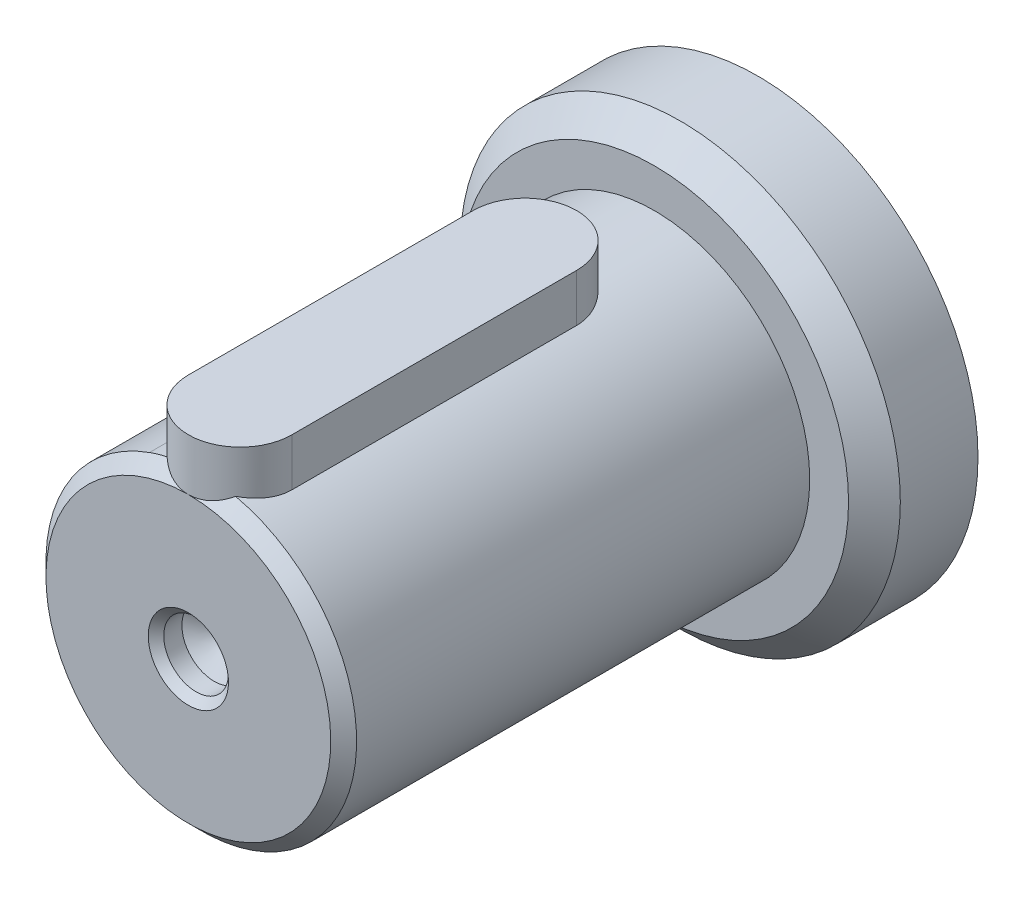
SolidWorks part; units mm, degrees
ref_plane "Plan de face" through (0, 0, 0) normal (0, 0, 1) x (1, 0, 0)
ref_plane "Plan de dessus" through (0, 0, 0) normal (0, 1, 0) x (1, 0, 0)
ref_plane "Plan de droite" through (0, 0, 0) normal (1, 0, 0) x (0, 0, -1)
sketch "Esquisse1" plane through (0, 0, 0) normal (0, 0, 1) x (1, 0, 0)
  circle A0 centre (0, 0) radius 8.5
  dimension "D1" = 17
extrude "Boss.-Extru.1" add sketch "Esquisse1" along normal blind 4
sketch "Esquisse2" plane through (0, 0, 4) normal (0, 0, 1) x (1, 0, 0)
  circle A0 centre (0, 0) radius 6
  dimension "D1" = 12
extrude "Boss.-Extru.2" add sketch "Esquisse2" along normal blind 18
chamfer "Chanfrein1" distance 1 angle 45 1 edges at (8.5, 0, 4)
chamfer "Chanfrein2" distance 0.5 angle 45 1 edges at (6, 0, 22)
ref_plane "Plan1" through (0, 6, 0) normal (0, 1, 0) x (1, 0, 0)
sketch "Esquisse3" plane through (0, 6, 0) normal (0, 1, 0) x (1, 0, 0)
  line L0 (0, -30.6066) -> (0, 7.4045) construction
  line L1 (0, -20) -> (0, -9) construction
  line L2 (-2, -20) -> (-2, -9)
  line L3 (2, -20) -> (2, -9)
  line L4 (-5.5, -22) -> (5.5, -22) construction
  line L5 (-9.0695, -7) -> (12.7701, -7) construction
  line L6 (-9.912, -22) -> (11.8854, -22) construction
  arc A0 (-2, -20) -> (2, -20) centre (0, -20) ccw
  arc A1 (2, -9) -> (-2, -9) centre (0, -9) ccw
  point P5 (0, -14.5)
  dimension "D1" = 4
  dimension "D2" = 15
extrude "Boss.-Extru.3" add sketch "Esquisse3" along normal blind 1.5 and the other way blind 1
hole_wizard "Trou pour taraudage pour trou taraudé M31" positions "Esquisse5" profile "Esquisse4" hole size "M3" standard "ISO"
sketch "Esquisse5" plane through (0, 0, 22) normal (0, 0, 1) x (1, 0, 0)
  point P0 (0, 0)
sketch "Esquisse4" plane through (0, 0, 22) normal (1, 0, 0) x (0, -1, 0)
  line L0 (0, 0) -> (0, 1.7511)
  line L1 (0, 1.7511) -> (1.25, 1)
  line L2 (1.25, 1) -> (1.25, 0)
  line L5 (1.25, 0) -> (0, 0)
  line L10 (0, 1.7511) -> (-1.25, 1) construction
  line L11 (0, -6.35) -> (0, 107.95) construction
  dimension "Diamètre du perçage" = 2.5
  dimension "Profondeur du perçage" = 1
  dimension "Angle de pointe" = 118
chamfer "Chanfrein3" distance 0.3 angle 45 1 edges at (1.25, 0, 22)
